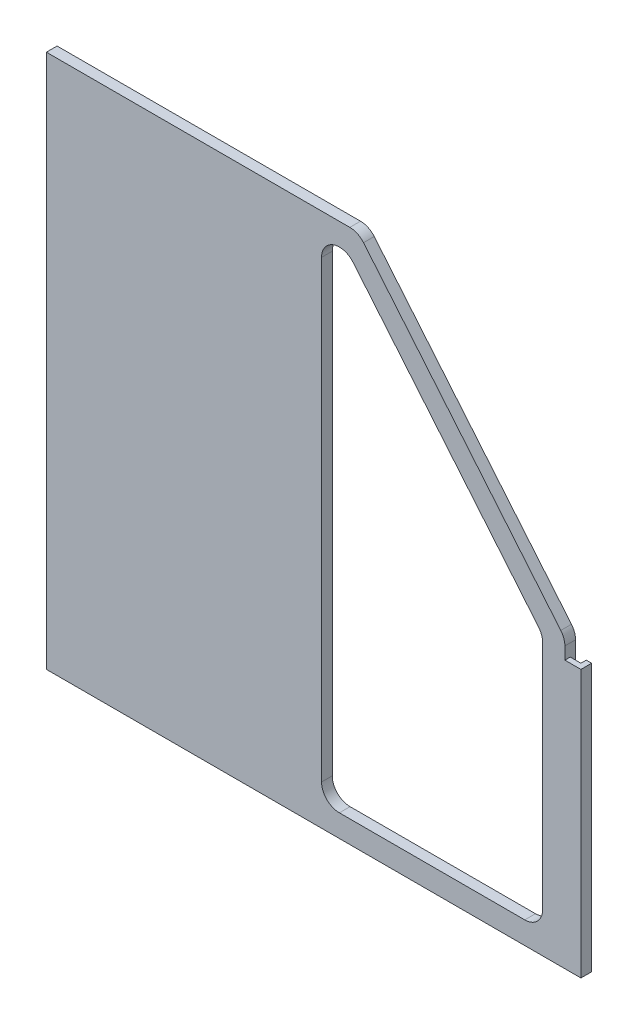
SolidWorks part; units mm, degrees
ref_plane "Front Plane" through (0, 0, 0) normal (0, 0, 1) x (1, 0, 0)
ref_plane "Top Plane" through (0, 0, 0) normal (0, 1, 0) x (1, 0, 0)
ref_plane "Right Plane" through (0, 0, 0) normal (1, 0, 0) x (0, 0, -1)
sketch "Sketch1" plane through (0, 0, 0) normal (0, 0, 1) x (1, 0, 0)
  line L0 (45.5622, 543.2263) -> (245.6772, 302.5847)
  line L1 (-310.4354, -49.5615) -> (289.5646, -49.5615)
  line L2 (-310.4354, -49.5615) -> (-310.4354, 550.4385)
  line L3 (-310.4354, 550.4385) -> (30.1846, 550.4385)
  line L4 (289.5646, -49.5615) -> (289.5646, 250.4385)
  line L5 (246.5646, 250.4385) -> (271.5646, 250.4385) construction
  line L6 (133.9245, -49.5615) -> (133.9245, -24.5615) construction
  line L7 (246.5646, 92.2126) -> (289.5646, 92.2126) construction
  line L8 (137.8897, 393.1014) -> (157.1117, 409.0862) construction
  line L9 (289.5646, 250.4385) -> (289.5646, 550.4385) construction
  line L10 (289.5646, 550.4385) -> (39.5646, 550.4385) construction
  line L11 (18.4595, 550.4385) -> (18.4595, 525.4385) construction
  line L12 (271.5646, 250.4385) -> (271.5646, 264.2253)
  line L13 (245.6772, 302.5847) -> (266.9422, 277.0132)
  line L14 (271.5646, 250.4385) -> (289.5646, 250.4385)
  line L16 (-26.5405, 275.7217) -> (-1.5405, 275.7217) construction
  line L18 (-1.5405, -4.5615) -> (-1.5405, 505.4385)
  line L27 (18.4595, -24.5615) -> (226.5646, -24.5615)
  line L28 (246.5646, -4.5615) -> (246.5646, 255.1886)
  line L29 (241.9422, 267.9765) -> (33.8371, 518.2263)
  arc A0 (18.4595, -24.5615) -> (-1.5405, -4.5615) centre (18.4595, -4.5615) cw
  arc A1 (226.5646, -24.5615) -> (246.5646, -4.5615) centre (226.5646, -4.5615) ccw
  arc A2 (241.9422, 267.9765) -> (246.5646, 255.1886) centre (226.5646, 255.1886) cw
  arc A3 (33.8371, 518.2263) -> (-1.5405, 505.4385) centre (18.4595, 505.4385) ccw
  arc A4 (30.1846, 550.4385) -> (45.5622, 543.2263) centre (30.1846, 530.4385) cw
  arc A5 (266.9422, 277.0132) -> (271.5646, 264.2253) centre (251.5646, 264.2253) cw
  point P25 (289.5646, 250.4385)
  dimension "D1" = 20
  dimension "D6" = 300
  dimension "D8" = 250
  dimension "D2" = 600
  dimension "D3" = 350
  dimension "D4" = 300
  dimension "D5" = 25
  dimension "D7" = 25
other "AlignGroup1"
extrude "Boss-Extrude1" add sketch "Sketch1" against normal blind 12
sketch "Sketch2" plane through (0, 0, -12) normal (0, 0, -1) x (-1, 0, 0)
  line L0 (-289.5646, 184.2067) -> (-283.5646, 184.2067) construction
  line L1 (-289.5646, -49.5615) -> (-289.5646, 250.4385) construction
  line L2 (-283.5646, 184.2067) -> (-271.5646, 184.2067) construction
  line L3 (-271.5646, 250.4385) -> (-271.5646, -49.5615)
  line L4 (310.4354, -49.5615) -> (-289.5646, -49.5615) construction
  line L5 (-283.5646, 250.4385) -> (-283.5646, -49.5615)
  line L6 (-289.5646, 250.4385) -> (-271.5646, 250.4385) construction
  line L7 (-283.5646, -49.5615) -> (-271.5646, -49.5615)
  line L8 (-283.5646, 250.4385) -> (-271.5646, 250.4385)
extrude "Cut-Extrude1" cut sketch "Sketch2" against normal blind 6
sketch "Sketch3" [suppressed] plane through (0, 0, 0) normal (0, 0, 1) x (1, 0, 0)
  line L0 (-310.4354, -49.5615) -> (289.5646, -49.5615) construction
  line L1 (271.5646, 250.4385) -> (283.5646, 250.4385)
  line L2 (271.5646, 250.4385) -> (271.5646, -49.5615)
  line L3 (271.5646, -49.5615) -> (283.5646, -49.5615)
  line L4 (283.5646, 250.4385) -> (283.5646, -49.5615)
  line L5 (271.5646, 218.2385) -> (283.5646, 218.2385) construction
  line L6 (283.5646, 218.2385) -> (289.5646, 218.2385) construction
  line L7 (289.5646, -49.5615) -> (289.5646, 250.4385) construction
  line L8 (289.5646, 250.4385) -> (271.5646, 250.4385) construction
extrude "Cut-Extrude2" [suppressed] cut sketch "Sketch3" against normal blind 6
